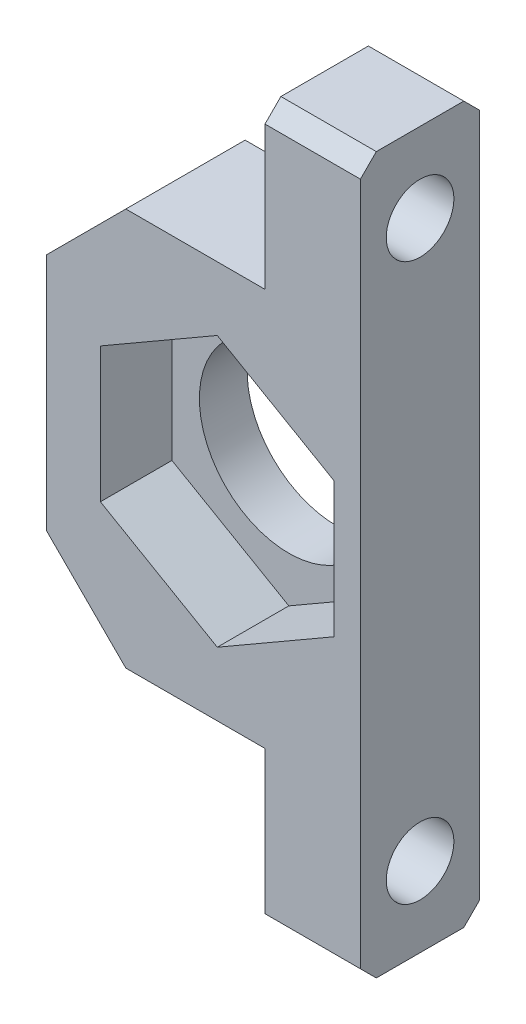
SolidWorks part; units mm, degrees
ref_plane "Front Plane" through (0, 0, 0) normal (0, 0, 1) x (1, 0, 0)
ref_plane "Top Plane" through (0, 0, 0) normal (0, 1, 0) x (1, 0, 0)
ref_plane "Right Plane" through (0, 0, 0) normal (1, 0, 0) x (0, 0, -1)
sketch "草图1" plane through (0, 0, 0) normal (0, 0, 1) x (1, 0, 0)
  line L1 (-52, 375.5065) -> (-79.4995, 375.5065)
  line L3 (-52, 325.5065) -> (-79.4995, 325.5065)
  line L4 (-79.4995, 375.5065) -> (-79.4995, 325.5065)
  line L5 (-40, 395.5065) -> (-40, 305.5065)
  line L8 (-40, 395.5065) -> (-52, 395.5065)
  line L9 (-52, 375.5065) -> (-52, 395.5065)
  line L12 (-40, 305.5065) -> (-52, 305.5065)
  line L13 (-52, 325.5065) -> (-52, 305.5065)
  circle A2 centre (-58, 350.5065) radius 11.25
  dimension "D8" = 22.5
  dimension "D2" = 18
  dimension "D1" = 50
  dimension "D5" = 20
  dimension "D7" = 90
extrude "凸台-拉伸1" add sketch "草图1" along normal blind 15
chamfer "倒角1" distance 10 angle 45 2 edges at (-79.4995, 325.5065, 7.5) (-79.4995, 375.5065, 7.5)
sketch "草图2" plane through (-52, 0, 0) normal (-1, 0, 0) x (0, 0, 1)
  line L0 (15, 395.5065) -> (0, 395.5065) construction
  line L1 (15, 305.5065) -> (0, 305.5065) construction
  circle A0 centre (7.5, 385.5065) radius 4.25
  circle A1 centre (7.5, 315.5065) radius 4.25
  dimension "D1" = 8.5
  dimension "D2" = 8.5
  dimension "D3" = 10
  dimension "D4" = 10
extrude "切除-拉伸1" cut sketch "草图2" against normal through all
sketch "草图3" plane through (0, 0, 15) normal (0, 0, 1) x (1, 0, 0)
  line L0 (-40, 305.5065) -> (-40, 395.5065) construction
  line L1 (-58, 367.4806) -> (-72.7, 358.9936)
  line L2 (-72.7, 358.9936) -> (-72.7, 342.0195)
  line L3 (-72.7, 342.0195) -> (-58, 333.5324)
  line L4 (-58, 333.5324) -> (-43.3, 342.0195)
  line L5 (-43.3, 342.0195) -> (-43.3, 358.9936)
  line L6 (-43.3, 358.9936) -> (-58, 367.4806)
  circle A0 centre (-58, 350.5065) radius 14.7 construction
  dimension "D1" = 29.4
extrude "切除-拉伸2" cut sketch "草图3" against normal blind 9
chamfer "倒角2" distance 2 angle 45 4 edges at (-46, 305.5065, 15) (-46, 305.5065, 0) (-46, 395.5065, 0) (-46, 395.5065, 15)
